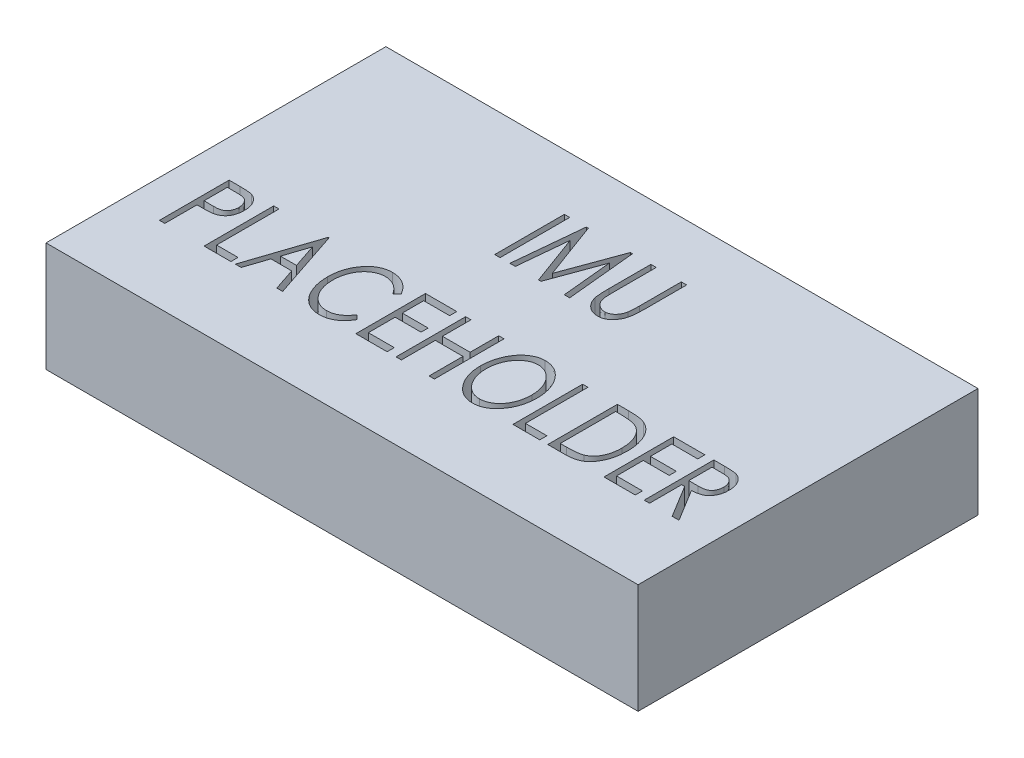
SolidWorks part; units mm, degrees
ref_plane "Front" through (0, 0, 0) normal (0, 0, 1) x (1, 0, 0)
ref_plane "Top" through (0, 0, 0) normal (0, 1, 0) x (1, 0, 0)
ref_plane "Right" through (0, 0, 0) normal (1, 0, 0) x (0, 0, -1)
sketch "Sketch1" plane through (0, 0, 0) normal (0, 1, 0) x (1, 0, 0)
  line L1 (-13.5, -7.75) -> (13.5, -7.75)
  line L2 (-13.5, -7.75) -> (-13.5, 7.75)
  line L3 (-13.5, 7.75) -> (13.5, 7.75)
  line L4 (13.5, -7.75) -> (13.5, 7.75)
  line L5 (-13.5, -7.75) -> (13.5, 7.75) construction
  line L6 (-13.5, 7.75) -> (13.5, -7.75) construction
  point P0 (0, 0)
  dimension "D1" = 15.5
  dimension "D2" = 27
extrude "Boss-Extrude1" add sketch "Sketch1" along normal blind 5
sketch "Sketch2" plane through (0, 5, 0) normal (0, 1, 0) x (1, 0, 0)
  line L0 (-13, 2.0209) -> (13, 2.0209) construction
  line L1 (-13, -2.0209) -> (13, -2.0209) construction
  line L2 (13, -2.0209) -> (13, 2.0209) construction
  line L3 (-13, 2.0209) -> (-13, -2.0209) construction
  line L4 (-13.5, 7.75) -> (-13.5, -7.75) construction
  line L5 (13.5, -7.75) -> (13.5, 7.75) construction
  text T0 "IMU\r\nPLACEHOLDER" font "Century Gothic" height in points 12
  point P9 (-13, 0)
  dimension "D1" = 0.5
  dimension "D2" = 0.5
extrude "Cut-Extrude2" cut sketch "Sketch2" against normal blind 2
